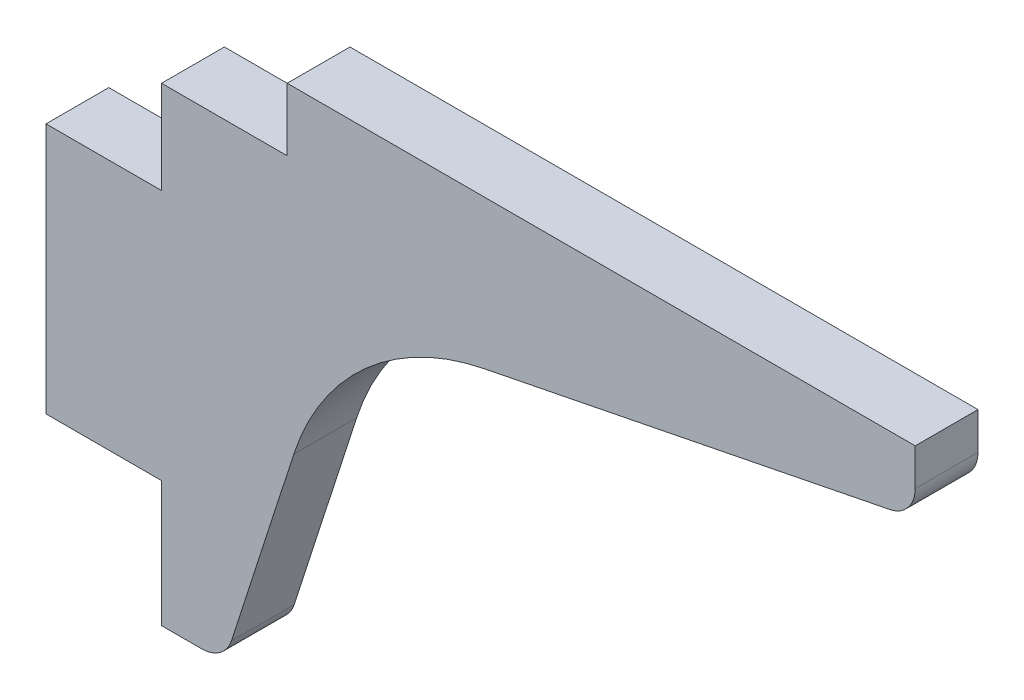
SolidWorks part; units mm, degrees
ref_plane "Front Plane" through (0, 0, 0) normal (0, 0, 1) x (1, 0, 0)
ref_plane "Top Plane" through (0, 0, 0) normal (0, 1, 0) x (1, 0, 0)
ref_plane "Right Plane" through (0, 0, 0) normal (1, 0, 0) x (0, 0, -1)
sketch "Sketch1" plane through (0, 0, 0) normal (0, 0, 1) x (1, 0, 0)
  line L0 (2.921, 6.35) -> (2.921, 11.049)
  line L1 (2.921, -6.35) -> (-2.921, -6.35)
  line L3 (2.921, 6.35) -> (-2.921, 6.35)
  line L4 (-2.921, -6.35) -> (-2.921, 6.35)
  line L5 (2.921, -6.35) -> (-2.921, 6.35) construction
  line L6 (2.921, 6.35) -> (-2.921, -6.35) construction
  line L7 (9.271, 14.224) -> (41.021, 14.224)
  line L8 (41.021, 14.224) -> (41.021, 11.049)
  line L9 (2.921, -6.35) -> (2.921, -12.7)
  line L10 (2.921, -12.7) -> (6.096, -12.7)
  line L11 (2.921, 14.224) -> (20.8815, -3.7365) construction
  line L12 (6.096, -12.7) -> (11.9013, 5.2437)
  line L13 (11.9013, 5.2437) -> (41.021, 11.049)
  line L16 (2.921, 11.049) -> (9.271, 11.049)
  line L17 (9.271, 14.224) -> (9.271, 11.049)
  point P0 (0, 0)
  dimension "D1" = 12.7
  dimension "D2" = 5.842
  dimension "D3" = 14.224
  dimension "D4" = 38.1
  dimension "D5" = 3.175
  dimension "D6" = 6.35
  dimension "D7" = 3.175
  dimension "D8" = 45
  dimension "D9" = 25.4
  dimension "D10" = 3.175
  dimension "D11" = 6.35
extrude "Boss-Extrude1" add sketch "Sketch1" along normal blind 3.175
fillet "Fillet1" radius 12.7 1 edges at (11.9013, 5.2437, 1.5875)
fillet "Fillet2" radius 1.5875 2 edges at (41.021, 11.049, 1.5875) (6.096, -12.7, 1.5875)
